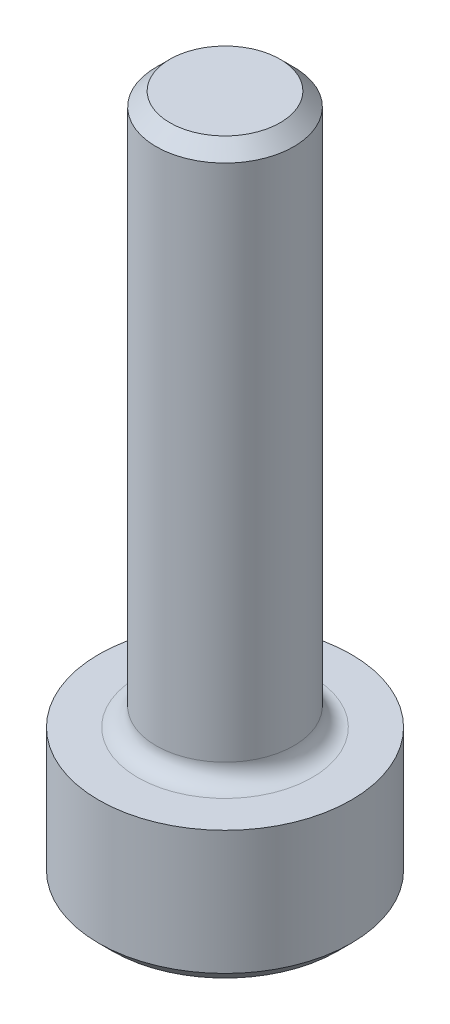
SolidWorks part; units mm, degrees
ref_plane "Front Plane" through (0, 0, 0) normal (0, 0, 1) x (1, 0, 0)
ref_plane "Top Plane" through (0, 0, 0) normal (0, 1, 0) x (1, 0, 0)
ref_plane "Right Plane" through (0, 0, 0) normal (1, 0, 0) x (0, 0, -1)
sketch "Sketch2" plane through (0, 0, 0) normal (0, 1, 0) x (1, 0, 0)
  circle A0 centre (0, 0) radius 1.5
extrude "Boss-Extrude1" add sketch "Sketch2" along normal blind 12
sketch "Sketch3" plane through (0, 0, 0) normal (0, 1, 0) x (1, 0, 0)
  circle A0 centre (0, 0) radius 2.75
  dimension "D1" = 5.5
extrude "Boss-Extrude2" add sketch "Sketch3" against normal blind 3
fillet "Fillet1" radius 0.4 1 edges at (0, 0, 1.5)
chamfer "Chamfer1" distance 0.3 angle 45 2 edges at (0, 12, 1.5) (0, -3, 2.75)
sketch "Sketch4" plane through (0, -3, 0) normal (0, -1, 0) x (1, 0, 0)
  line L1 (0, 1.4434) -> (-1.25, 0.7217)
  line L2 (-1.25, 0.7217) -> (-1.25, -0.7217)
  line L3 (-1.25, -0.7217) -> (0, -1.4434)
  line L4 (0, -1.4434) -> (1.25, -0.7217)
  line L5 (1.25, -0.7217) -> (1.25, 0.7217)
  line L6 (1.25, 0.7217) -> (0, 1.4434)
  circle A0 centre (0, 0) radius 1.25 construction
  dimension "D1" = 2.5
extrude "Cut-Extrude1" cut sketch "Sketch4" against normal blind 2.5
